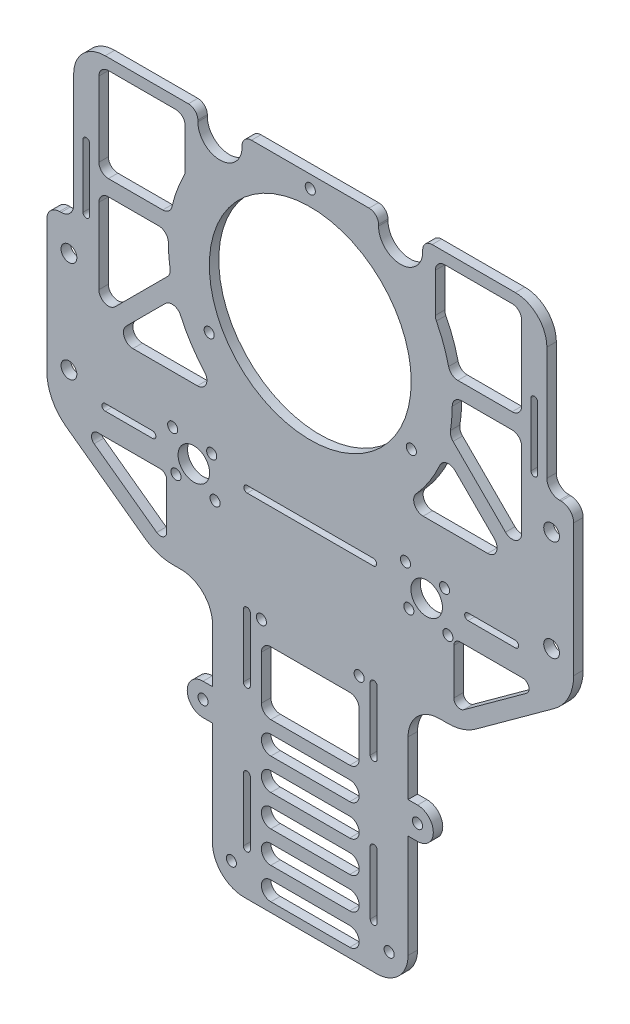
SolidWorks part; units mm, degrees
material "A-玻璃纤维"
ref_plane "前视基准面" through (0, 0, 0) normal (0, 0, 1) x (1, 0, 0)
ref_plane "上视基准面" through (0, 0, 0) normal (0, 1, 0) x (1, 0, 0)
ref_plane "右视基准面" through (0, 0, 0) normal (1, 0, 0) x (0, 0, -1)
sketch "草图1" plane through (0, 0, 0) normal (0, 0, 1) x (1, 0, 0)
  line L0 (-39.5, 92.55) -> (39.5, 92.55)
  line L1 (39.5, 92.55) -> (75, 72.0541)
  line L2 (75, 72.0541) -> (75, -9)
  line L3 (75, -9) -> (83.5, -9)
  line L4 (83.5, -9) -> (83.5, -88)
  line L5 (83.5, -88) -> (31, -88)
  line L6 (31, -88) -> (31, -115.2)
  line L7 (31, -115.2) -> (34, -115.2)
  line L8 (34, -125.2) -> (31, -125.2)
  line L9 (31, -125.2) -> (31, -168)
  line L10 (31, -168) -> (-31, -168)
  line L11 (-31, -168) -> (-31, -125.2)
  line L12 (-31, -125.2) -> (-34, -125.2)
  line L13 (-34, -115.2) -> (-31, -115.2)
  line L14 (-31, -115.2) -> (-31, -88)
  line L15 (-31, -88) -> (-83.5, -88)
  line L16 (-83.5, -88) -> (-83.5, -9)
  line L17 (-83.5, -9) -> (-75, -9)
  line L18 (-75, -9) -> (-75, 72.0541)
  line L19 (-75, 72.0541) -> (-39.5, 92.55)
  line L20 (0, 109.1196) -> (0, -307.0032) construction
  circle A0 centre (0, 0) radius 32
  arc A1 (34, -115.2) -> (34, -125.2) centre (34, -120.2) cw
  arc A2 (-34, -125.2) -> (-34, -115.2) centre (-34, -120.2) cw
  circle A3 centre (-34, -120.2) radius 1.6
  circle A4 centre (34, -120.2) radius 1.6
  dimension "D10" = 64
  dimension "D13" = 5
  dimension "D14" = 3.2
  dimension "D15" = 3.2
  dimension "D2" = 150
  dimension "D3" = 167
  dimension "D4" = 62
  dimension "D5" = 80
  dimension "D6" = 79
  dimension "D7" = 88
  dimension "D8" = 79
  dimension "D9" = 150
  dimension "D11" = 3
  dimension "D12" = 47.8
  dimension "D16" = 180.55
extrude "基本板" add sketch "草图1" along normal blind 3
sketch "草图2" plane through (0, 0, 3) normal (0, 0, 1) x (1, 0, 0)
  line L0 (-12.5, -162) -> (12.5, -162) construction
  line L1 (-12.5, -159) -> (12.5, -159)
  line L2 (-12.5, -165) -> (12.5, -165)
  line L3 (-31, -168) -> (31, -168) construction
  line L4 (-12.5, -152) -> (12.5, -152) construction
  line L5 (-12.5, -149) -> (12.5, -149)
  line L6 (-12.5, -155) -> (12.5, -155)
  line L7 (-12.5, -142) -> (12.5, -142) construction
  line L8 (-12.5, -139) -> (12.5, -139)
  line L9 (-12.5, -145) -> (12.5, -145)
  line L10 (-12.5, -132) -> (12.5, -132) construction
  line L11 (-12.5, -129) -> (12.5, -129)
  line L12 (-12.5, -135) -> (12.5, -135)
  line L13 (-12.5, -122) -> (12.5, -122) construction
  line L14 (-12.5, -119) -> (12.5, -119)
  line L15 (-12.5, -125) -> (12.5, -125)
  line L16 (-12.5, -112) -> (12.5, -112) construction
  line L18 (-12.5, -115) -> (12.5, -115)
  line L22 (-15.5, -112) -> (-15.5, -98)
  line L23 (-12.5, -95) -> (12.5, -95)
  line L24 (15.5, -98) -> (15.5, -112)
  line L28 (0, 134.0686) -> (0, -266.1855) construction
  line L35 (-67, 42.4353) -> (-39.64, 42.4353)
  line L36 (-67, 37.4353) -> (-39.64, 37.4353)
  line L37 (-67, 7.7753) -> (-44.3232, 7.7753)
  line L38 (-67, 2.7753) -> (-44.9143, 2.7753)
  line L39 (-67, -35) -> (-43.5045, -11.5045) construction
  line L40 (-67, -31.4645) -> (-44.1649, -8.6293)
  line L41 (-63.4645, -35) -> (-42.6917, -14.2273)
  line L42 (-67, 7.7753) -> (-67, 37.4353)
  line L43 (-67, 42.4353) -> (-67, 67.4353)
  line L44 (-39.64, 37.4353) -> (-39.64, 21.2995)
  line L45 (28.2843, -35) -> (63.4645, -35)
  line L46 (63.4645, -35) -> (42.6917, -14.2273)
  line L47 (67, -31.4645) -> (67, 2.7753)
  line L48 (67, -31.4645) -> (44.1649, -8.6293)
  line L49 (67, 2.7753) -> (44.9143, 2.7753)
  line L50 (67, 7.7753) -> (44.3232, 7.7753)
  line L51 (67, 7.7753) -> (67, 37.4353)
  line L52 (39.64, 37.4353) -> (39.64, 21.2995)
  line L53 (67, 37.4353) -> (39.64, 37.4353)
  line L54 (-28.2843, -35) -> (-63.4645, -35)
  line L55 (-67, -31.4645) -> (-67, 2.7753)
  line L56 (-67, 67.4353) -> (-39.64, 83.2316)
  line L57 (-39.64, 83.2316) -> (-39.64, 42.4353)
  line L58 (-75, 72.0541) -> (-75, -9) construction
  line L59 (-39.5, 92.55) -> (-75, 72.0541) construction
  line L60 (-28.64, 75.55) -> (-28.64, 37.55) construction
  line L61 (-21.64, 75.55) -> (-21.64, 37.55)
  line L62 (-35.64, 75.55) -> (-35.64, 37.55)
  line L63 (-9.64, 75.55) -> (-9.64, 37.55) construction
  line L64 (-2.64, 75.55) -> (-2.64, 44.9225)
  line L65 (-16.64, 75.55) -> (-16.64, 41.8104)
  line L66 (39.5, 92.55) -> (-39.5, 92.55) construction
  line L67 (67, 42.4353) -> (39.64, 42.4353)
  line L68 (67, 42.4353) -> (67, 67.4353)
  line L69 (67, 67.4353) -> (39.64, 83.2316)
  line L70 (39.64, 83.2316) -> (39.64, 42.4353)
  line L71 (28.64, 75.55) -> (28.64, 37.55) construction
  line L72 (21.64, 75.55) -> (21.64, 37.55)
  line L73 (35.64, 75.55) -> (35.64, 37.55)
  line L74 (2.64, 75.55) -> (2.64, 44.9225)
  line L75 (16.64, 75.55) -> (16.64, 41.8104)
  arc A0 (-12.5, -159) -> (-12.5, -165) centre (-12.5, -162) ccw
  arc A1 (12.5, -165) -> (12.5, -159) centre (12.5, -162) ccw
  arc A2 (-12.5, -149) -> (-12.5, -155) centre (-12.5, -152) ccw
  arc A3 (12.5, -155) -> (12.5, -149) centre (12.5, -152) ccw
  arc A4 (-12.5, -139) -> (-12.5, -145) centre (-12.5, -142) ccw
  arc A5 (12.5, -145) -> (12.5, -139) centre (12.5, -142) ccw
  arc A6 (-12.5, -129) -> (-12.5, -135) centre (-12.5, -132) ccw
  arc A7 (12.5, -135) -> (12.5, -129) centre (12.5, -132) ccw
  arc A8 (-12.5, -119) -> (-12.5, -125) centre (-12.5, -122) ccw
  arc A9 (12.5, -125) -> (12.5, -119) centre (12.5, -122) ccw
  arc A10 (-15.5, -112) -> (-12.5, -115) centre (-12.5, -112) ccw
  arc A11 (12.5, -115) -> (15.5, -112) centre (12.5, -112) ccw
  arc A14 (-15.5, -98) -> (-12.5, -95) centre (-12.5, -98) cw
  arc A15 (12.5, -95) -> (15.5, -98) centre (12.5, -98) cw
  arc A18 (-39.64, 21.2995) -> (-44.3232, 7.7753) centre (0, 0) ccw
  arc A19 (-21.64, 75.55) -> (-35.64, 75.55) centre (-28.64, 75.55) ccw
  arc A20 (-35.64, 37.55) -> (-21.64, 37.55) centre (-28.64, 37.55) ccw
  arc A21 (-2.64, 75.55) -> (-16.64, 75.55) centre (-9.64, 75.55) ccw
  arc A22 (-42.6917, -14.2273) -> (-28.2843, -35) centre (0, 0) ccw
  arc A23 (-44.9143, 2.7753) -> (-44.1649, -8.6293) centre (0, 0) ccw
  arc A24 (-2.64, 44.9225) -> (-16.64, 41.8104) centre (0, 0) ccw
  arc A25 (42.6917, -14.2273) -> (28.2843, -35) centre (0, 0) cw
  arc A26 (44.9143, 2.7753) -> (44.1649, -8.6293) centre (0, 0) cw
  arc A27 (39.64, 21.2995) -> (44.3232, 7.7753) centre (0, 0) cw
  arc A28 (21.64, 75.55) -> (35.64, 75.55) centre (28.64, 75.55) cw
  arc A29 (35.64, 37.55) -> (21.64, 37.55) centre (28.64, 37.55) cw
  arc A30 (2.64, 44.9225) -> (16.64, 41.8104) centre (0, 0) cw
  arc A31 (2.64, 75.55) -> (16.64, 75.55) centre (9.64, 75.55) cw
  point P2 (0, -162)
  point P7 (0, -64.75)
  point P14 (0, -152)
  point P21 (0, -142)
  point P28 (0, -132)
  point P35 (0, -122)
  point P42 (0, -112)
  point P56 (0, -119)
  point P63 (0, -109)
  point P84 (-28.64, 56.55)
  point P89 (-9.495, 56.55)
  point P134 (28.64, 56.55)
  point P146 (0, -119)
  point P151 (0, -109)
  point P159 (0, -109)
  point P166 (0, -119)
  point P173 (0, -109)
  point P180 (0, -119)
  point P187 (0, -109)
  point P194 (0, -119)
  point P201 (0, -109)
  point P208 (0, -119)
  point P215 (0, -109)
  point P222 (0, -119)
  point P229 (0, -109)
  point P236 (0, -119)
  point P243 (0, -109)
  point P250 (0, -119)
  point P257 (0, -109)
  point P264 (0, -119)
  point P271 (0, -109)
  point P278 (0, -119)
  point P285 (0, -81)
  point P292 (0, -91)
  point P299 (0, -81)
  point P306 (0, -91)
  point P313 (0, -81)
  point P320 (0, -91)
  point P327 (0, -81)
  point P334 (0, -91)
  dimension "D8" = 90
  dimension "D19" = 7
  dimension "D1" = 25
  dimension "D2" = 3
  dimension "D3" = 6
  dimension "D9" = 35
  dimension "D10" = 27.36
  dimension "D11" = 8
  dimension "D12" = 8
  dimension "D13" = 38
  dimension "D14" = 14
  dimension "D15" = 17
  dimension "D16" = 4
  dimension "D17" = 5
  dimension "D18" = 14
  dimension "D20" = 45
  dimension "D21" = 5
  dimension "D22" = 2.5
  dimension "D23" = 5
  dimension "D24" = 5
  dimension "D25" = 25
  dimension "D26" = 29.66
  dimension "D27" = 20
  dimension "D28" = 10
  dimension "D29" = 4
  dimension "D30" = 31
  dimension "D4" = 5
extrude "减重镂空" cut sketch "草图2" against normal blind 3
sketch "草图3" plane through (0, 0, 3) normal (0, 0, 1) x (1, 0, 0)
  circle A0 centre (0, 0) radius 37 construction
  circle A1 centre (0, 37) radius 1.6
  circle A2 centre (32.0429, -18.5) radius 1.6
  circle A3 centre (-32.0429, -18.5) radius 1.6
  circle A4 centre (-15.5, -89) radius 1.6
  circle A5 centre (15.5, -89) radius 1.6
  point P12 (0, 0)
  dimension "D1" = 74
  dimension "D2" = 3.2
  dimension "D4" = 31
  dimension "D7" = 3.2
  dimension "D8" = 3.2
  dimension "D5" = 89
  dimension "D6" = 15.5
  dimension "D3" = 3
extrude "拨弹盘固定孔" cut sketch "草图3" against normal blind 3
sketch "草图5" plane through (0, 0, 3) normal (0, 0, 1) x (1, 0, 0)
  line L0 (-27.5, 85.09) -> (27.5, 85.09) construction
  line L1 (-27.5, 86.14) -> (27.5, 86.14)
  line L2 (-27.5, 84.04) -> (27.5, 84.04)
  line L3 (39.5, 92.55) -> (-39.5, 92.55) construction
  line L4 (71, 14.5) -> (71, -5.5) construction
  line L5 (72.05, 14.5) -> (72.05, -5.5)
  line L6 (69.95, 14.5) -> (69.95, -5.5)
  line L7 (75, -9) -> (75, 72.0541) construction
  line L8 (71, 64.5) -> (71, 44.5) construction
  line L9 (72.05, 64.5) -> (72.05, 44.5)
  line L10 (69.95, 64.5) -> (69.95, 44.5)
  line L11 (50, -55.5) -> (65, -55.5) construction
  line L12 (50, -54.45) -> (65, -54.45)
  line L13 (50, -56.55) -> (65, -56.55)
  line L16 (0, 114.463) -> (0, -242.1997) construction
  line L17 (-71, 64.5) -> (-71, 44.5) construction
  line L18 (-72.05, 64.5) -> (-72.05, 44.5)
  line L19 (-69.95, 64.5) -> (-69.95, 44.5)
  line L20 (-71, 14.5) -> (-71, -5.5) construction
  line L21 (-72.05, 14.5) -> (-72.05, -5.5)
  line L22 (-69.95, 14.5) -> (-69.95, -5.5)
  line L23 (-50, -55.5) -> (-65, -55.5) construction
  line L24 (-50, -54.45) -> (-65, -54.45)
  line L25 (-50, -56.55) -> (-65, -56.55)
  line L26 (-20, -55.5) -> (20, -55.5) construction
  line L27 (-20, -54.45) -> (20, -54.45)
  line L28 (-20, -56.55) -> (20, -56.55)
  line L29 (-83.5, -9) -> (-83.5, -88) construction
  line L30 (31, -88) -> (83.5, -88) construction
  arc A0 (-27.5, 86.14) -> (-27.5, 84.04) centre (-27.5, 85.09) ccw
  arc A1 (27.5, 84.04) -> (27.5, 86.14) centre (27.5, 85.09) ccw
  arc A2 (72.05, 14.5) -> (69.95, 14.5) centre (71, 14.5) ccw
  arc A3 (69.95, -5.5) -> (72.05, -5.5) centre (71, -5.5) ccw
  arc A4 (72.05, 64.5) -> (69.95, 64.5) centre (71, 64.5) ccw
  arc A5 (69.95, 44.5) -> (72.05, 44.5) centre (71, 44.5) ccw
  arc A6 (50, -54.45) -> (50, -56.55) centre (50, -55.5) ccw
  arc A7 (65, -56.55) -> (65, -54.45) centre (65, -55.5) ccw
  arc A8 (-72.05, 64.5) -> (-69.95, 64.5) centre (-71, 64.5) cw
  arc A9 (-69.95, 44.5) -> (-72.05, 44.5) centre (-71, 44.5) cw
  arc A10 (-72.05, 14.5) -> (-69.95, 14.5) centre (-71, 14.5) cw
  arc A11 (-69.95, -5.5) -> (-72.05, -5.5) centre (-71, -5.5) cw
  arc A12 (-50, -54.45) -> (-50, -56.55) centre (-50, -55.5) cw
  arc A13 (-65, -56.55) -> (-65, -54.45) centre (-65, -55.5) cw
  arc A14 (-20, -54.45) -> (-20, -56.55) centre (-20, -55.5) ccw
  arc A15 (20, -56.55) -> (20, -54.45) centre (20, -55.5) ccw
  point P2 (0, 85.09)
  point P9 (71, 4.5)
  point P21 (71, 54.5)
  point P28 (57.5, -55.5)
  point P41 (-71, 54.5)
  point P48 (-71, 4.5)
  point P55 (-57.5, -55.5)
  point P62 (0, -55.5)
  dimension "D10" = 1.05
  dimension "D1" = 55
  dimension "D2" = 2.1
  dimension "D3" = 6.41
  dimension "D4" = 4
  dimension "D5" = 20
  dimension "D6" = 2.1
  dimension "D7" = 4.5
  dimension "D9" = 15
  dimension "D11" = 18.5
  dimension "D12" = 32.5
  dimension "D13" = 2.1
  dimension "D14" = 40
  dimension "D8" = 2
extrude "弹仓固定槽" cut sketch "草图5" against normal blind 10
sketch "草图6" plane through (0, 0, 3) normal (0, 0, 1) x (1, 0, 0)
  line L0 (-83.5, -9) -> (-83.5, -88) construction
  line L1 (0, 130.6253) -> (0, -251.0224) construction
  circle A0 centre (-76.5, -19) radius 2.5
  circle A1 centre (-76.5, -51) radius 2.5
  circle A2 centre (0, 0) radius 32 construction
  circle A3 centre (76.5, -19) radius 2.5
  circle A4 centre (76.5, -51) radius 2.5
  dimension "D1" = 32
  dimension "D2" = 5
  dimension "D3" = 7
  dimension "D4" = 19
extrude "支座孔" cut sketch "草图6" against normal blind 3
sketch "草图8" plane through (0, 0, 3) normal (0, 0, 1) x (1, 0, 0)
  line L0 (30.1825, -50.2825) -> (43.6175, -63.7175) construction
  line L1 (31.2431, -62.6569) -> (42.5569, -51.3431) construction
  line L2 (25.4491, -57) -> (58.1433, -57) construction
  circle A0 centre (36.9, -57) radius 5
  circle A1 centre (42.5569, -51.3431) radius 1.6
  circle A2 centre (31.2431, -62.6569) radius 1.6
  circle A3 centre (30.1825, -50.2825) radius 1.6
  circle A4 centre (43.6175, -63.7175) radius 1.6
  circle A5 centre (-43.6175, -50.2825) radius 1.6
  circle A6 centre (-36.9, -57) radius 5
  circle A7 centre (-42.5569, -62.6569) radius 1.6
  circle A8 centre (-30.1825, -63.7175) radius 1.6
  circle A9 centre (-31.2431, -51.3431) radius 1.6
  dimension "D1" = 10
  dimension "D2" = 3.2
  dimension "D3" = 8
  dimension "D4" = 57
  dimension "D5" = 3.2
  dimension "D6" = 45
  dimension "D7" = 9.5
  dimension "D8" = 36.9
  dimension "D10" = 73.8
  dimension "D9" = 2
extrude "摩擦轮电机固定孔" cut sketch "草图8" against normal blind 3
fillet "圆角1" radius 10 6 edges at (83.5, -88, 1.5) (-83.5, -88, 1.5) (31, -88, 1.5) (-31, -88, 1.5) (-31, -168, 1.5) (31, -168, 1.5)
fillet "圆角2" radius 15 4 edges at (75, 72.0541, 1.5) (39.5, 92.55, 1.5) (-39.5, 92.55, 1.5) (-75, 72.0541, 1.5)
fillet "圆角4" radius 3 36 edges at (-16.64, 41.8104, 1.5) (-2.64, 44.9225, 1.5) (2.64, 44.9225, 1.5) (16.64, 41.8104, 1.5) (28.2843, -35, 1.5) (63.4645, -35, 1.5) (42.6917, -14.2273, 1.5) (44.1649, -8.6293, 1.5) (67, -31.4645, 1.5) (67, 2.7753, 1.5) (44.9143, 2.7753, 1.5) (44.3232, 7.7753, 1.5) (39.64, 21.2995, 1.5) (39.64, 37.4353, 1.5) (67, 37.4353, 1.5) (67, 7.7753, 1.5) (67, 42.4353, 1.5) (67, 67.4353, 1.5) (39.64, 42.4353, 1.5) (39.64, 83.2316, 1.5) (-67, 67.4353, 1.5) (-39.64, 83.2316, 1.5) (-67, 42.4353, 1.5) (-39.64, 42.4353, 1.5) (-39.64, 37.4353, 1.5) (-67, 37.4353, 1.5) (-67, 7.7753, 1.5) (-44.3232, 7.7753, 1.5) (-39.64, 21.2995, 1.5) (-44.1649, -8.6293, 1.5) (-44.9143, 2.7753, 1.5) (-67, 2.7753, 1.5) (-67, -31.4645, 1.5) (-28.2843, -35, 1.5) (-42.6917, -14.2273, 1.5) (-63.4645, -35, 1.5)
sketch "草图9" plane through (0, 0, 3) normal (0, 0, 1) x (1, 0, 0)
  line L0 (20.1, -89) -> (20.1, -109) construction
  line L1 (21.2, -89) -> (21.2, -109)
  line L2 (19, -89) -> (19, -109)
  line L3 (20.1, -134) -> (20.1, -154) construction
  line L4 (21.2, -134) -> (21.2, -154)
  line L5 (19, -134) -> (19, -154)
  line L6 (0, 143.7439) -> (0, -273.8338) construction
  line L7 (31, -158) -> (31, -125.2) construction
  line L8 (-21, -168) -> (21, -168) construction
  line L9 (-20.1, -134) -> (-20.1, -154) construction
  line L10 (-21.2, -134) -> (-21.2, -154)
  line L11 (-19, -134) -> (-19, -154)
  line L12 (-20.1, -89) -> (-20.1, -109) construction
  line L13 (-21.2, -89) -> (-21.2, -109)
  line L14 (-19, -89) -> (-19, -109)
  arc A0 (21.2, -89) -> (19, -89) centre (20.1, -89) ccw
  arc A1 (19, -109) -> (21.2, -109) centre (20.1, -109) ccw
  arc A2 (21.2, -134) -> (19, -134) centre (20.1, -134) ccw
  arc A3 (19, -154) -> (21.2, -154) centre (20.1, -154) ccw
  arc A4 (-21.2, -134) -> (-19, -134) centre (-20.1, -134) cw
  arc A5 (-19, -154) -> (-21.2, -154) centre (-20.1, -154) cw
  arc A6 (-21.2, -89) -> (-19, -89) centre (-20.1, -89) cw
  arc A7 (-19, -109) -> (-21.2, -109) centre (-20.1, -109) cw
  point P2 (20.1, -99)
  point P7 (20.1, -144)
  point P23 (-20.1, -144)
  point P30 (-20.1, -99)
  dimension "D1" = 2.2
  dimension "D2" = 12
  dimension "D3" = 20
  dimension "D4" = 59
  dimension "D5" = 45
  dimension "D6" = 20
extrude "摄像头保护板槽" cut sketch "草图9" against normal blind 3
sketch "草图10" plane through (0, 0, 3) normal (0, 0, 1) x (1, 0, 0)
  line L0 (31, -158) -> (31, -125.2) construction
  line L1 (-21, -168) -> (21, -168) construction
  line L2 (-31, -125.2) -> (-31, -158) construction
  circle A0 centre (25, -160) radius 1.6
  circle A1 centre (-25, -160) radius 1.6
  dimension "D1" = 3.2
  dimension "D4" = 3.2
  dimension "D2" = 6
  dimension "D3" = 8
  dimension "D5" = 6
extrude "测速模块加固孔" cut sketch "草图10" against normal blind 3
fillet "圆角5" radius 4 4 edges at (-75, -9, 1.5) (-83.5, -9, 1.5) (83.5, -9, 1.5) (75, -9, 1.5)
sketch "草图11" plane through (0, 0, 3) normal (0, 0, 1) x (1, 0, 0)
  line L0 (48.5, -88) -> (83.5, -62.571)
  line L1 (41, -88) -> (73.5, -88) construction
  line L2 (83.5, -78) -> (83.5, -13) construction
  line L3 (83.5, -62.571) -> (83.5, -88)
  line L4 (83.5, -88) -> (48.5, -88)
  line L5 (0, 123.0796) -> (0, -208.4052) construction
  line L6 (-83.5, -88) -> (-48.5, -88)
  line L7 (-83.5, -62.571) -> (-83.5, -88)
  line L8 (-48.5, -88) -> (-83.5, -62.571)
  circle A0 centre (36.9, -57) radius 30 construction
  dimension "D3" = 60
  dimension "D1" = 36
  dimension "D2" = 35
extrude "切除-拉伸1" cut sketch "草图11" against normal through all
sketch "草图12" plane through (0, 0, 3) normal (0, 0, 1) x (1, 0, 0)
  line L0 (-75, 63.3938) -> (-75, -5) construction
  line L1 (75, 101.9454) -> (-75, 101.9454)
  line L2 (75, 101.9454) -> (75, 41)
  line L3 (75, 41) -> (-75, 41)
  line L4 (-75, 101.9454) -> (-75, 41)
  line L5 (0, 41) -> (0, 101.9454) construction
  line L6 (75, 71.4727) -> (-75, 71.4727) construction
  line L7 (75, -5) -> (75, 63.3938) construction
  point P0 (0, 71.4727)
  dimension "D1" = 41
extrude "切除-拉伸2" cut sketch "草图12" against normal blind 10
fillet "圆角6" radius 15 4 edges at (-83.5, -62.571, 1.5) (83.5, -62.571, 1.5) (48.5, -88, 1.5) (-48.5, -88, 1.5)
fillet "圆角7" radius 10 2 edges at (-75, 41, 1.5) (75, 41, 1.5)
fillet "圆角8" radius 3 4 edges at (35.64, 41, 1.5) (21.64, 41, 1.5) (-21.64, 41, 1.5) (-35.64, 41, 1.5)
sketch "草图13" plane through (0, 0, 0) normal (0, 0, -1) x (-1, 0, 0)
  line L0 (45.5, -83.9993) -> (73.5, -63.6561)
  line L1 (73.5, -63.6561) -> (45.5, -63.6561)
  line L2 (45.5, -63.6561) -> (45.5, -83.9993)
  line L3 (0, -185.2719) -> (0, 53.4982) construction
  line L4 (52.443, -85.1353) -> (77.3168, -67.0634) construction
  line L5 (83.5, -13) -> (83.5, -54.9281) construction
  line L6 (-45.5, -63.6561) -> (-45.5, -83.9993)
  line L7 (-73.5, -63.6561) -> (-45.5, -63.6561)
  line L8 (-45.5, -83.9993) -> (-73.5, -63.6561)
  dimension "D1" = 5
  dimension "D2" = 10
  dimension "D3" = 28
extrude "切除-拉伸3" cut sketch "草图13" against normal through all
fillet "圆角9" radius 2 6 edges at (45.5, -83.9993, 1.5) (73.5, -63.6561, 1.5) (45.5, -63.6561, 1.5) (-45.5, -63.6561, 1.5) (-45.5, -83.9993, 1.5) (-73.5, -63.6561, 1.5)
